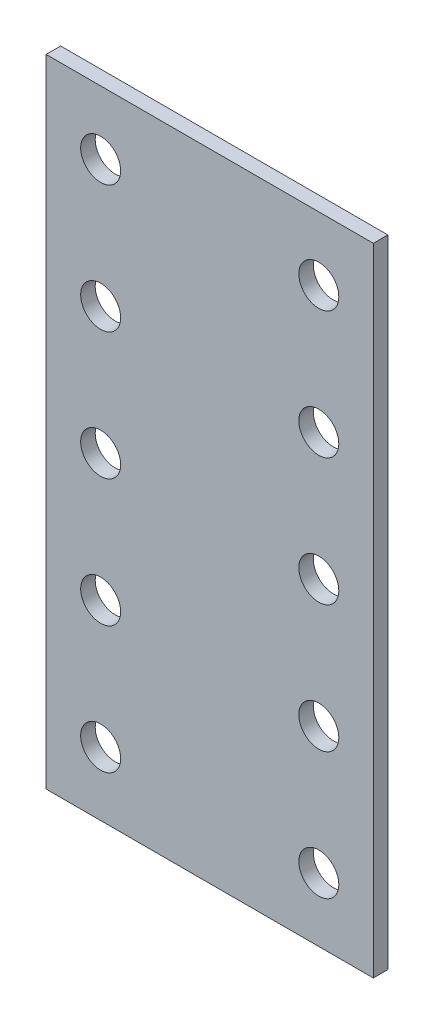
SolidWorks part; units mm, degrees
other "Connection Feature" parameters "Plate Thickness"=8
ref_plane "Front Plane" through (0, 0, 0) normal (0, 0, 1) x (1, 0, 0)
ref_plane "Top Plane" through (0, 0, 0) normal (0, 1, 0) x (1, 0, 0)
ref_plane "Right Plane" through (0, 0, 0) normal (1, 0, 0) x (0, 0, -1)
sketch "Sketch1" plane through (0, 0, 0) normal (0, 0, 1) x (1, 0, 0)
  line L1 (-90, -175) -> (90, -175)
  line L2 (-90, -175) -> (-90, 175)
  line L3 (-90, 175) -> (90, 175)
  line L4 (90, -175) -> (90, 175)
  line L5 (-90, -175) -> (90, 175) construction
  line L6 (-90, 175) -> (90, -175) construction
  point P0 (0, 0)
  dimension "Plate Width" = 180
  dimension "Length" = 350
extrude "Boss-Extrude1" add sketch "Sketch1" against normal mid plane 8
sketch "Sketch4" plane through (0, 0, 4) normal (0, 0, 1) x (1, 0, 0)
  line L0 (0, 175) -> (0, -175) construction
  line L1 (90, 175) -> (-90, 175) construction
  line L2 (-90, -175) -> (90, -175) construction
  point P0 (-60, 140)
  point P2 (60, 140)
  dimension "Hole Centre to Centre" = 120
  dimension "Hole End Distance" = 35
hole_wizard "Ø22.0 (22) Diameter Hole1" positions "Sketch4" profile "Sketch3" hole size "Ø22.0" standard "ISO" end condition up to next
sketch "Sketch3" plane through (-60, 140, 4) normal (1, 0, 0) x (0, -1, 0)
  line L0 (0, 0) -> (0, 8)
  line L1 (0, 8) -> (11, 8)
  line L2 (11, 8) -> (11, 0)
  line L5 (11, 0) -> (0, 0)
  line L11 (0, -6.35) -> (0, 107.95) construction
  dimension "Thru Hole Dia." = 22
  dimension "Thru Hole Depth" = 8
pattern_linear "LPattern1" count 5 spacing 70 along (0, -1, 0) of "Ø22.0 (22) Diameter Hole1"
equation "\"Hole Dia\"=22"
equation "\"Hole Centre to Center\"=120"
equation "\"Hole End Distance\"=35"
equation "\"Hole Pitch\"=70"
equation "\"Number of Rows\"= 5"
equation "\"Plate Length\"= \"Hole End Distance\" * 2 + ( \"Number of Rows\" - 1 ) * \"Hole Pitch\""
equation "\"Length@Sketch1\"=\"Plate Length\""
equation "\"Thru Hole Dia.@Sketch3\"= \"Hole Dia\""
equation "\"Hole Centre to Centre@Sketch4\"= \"Hole Centre to Center\""
equation "\"Hole End Distance@Sketch4\"= \"Hole End Distance\""
equation "\"Hole Pitch@LPattern1\"= \"Hole Pitch\""
equation "\"Number of Rows@LPattern1\"= \"Number of Rows\""
equation "\"Plate Width\"=180"
equation "\"Plate Width@Sketch1\"= \"Plate Width\""
equation "\"Thru Hole Depth@Sketch3\"= \"RD1@Annotations\""
